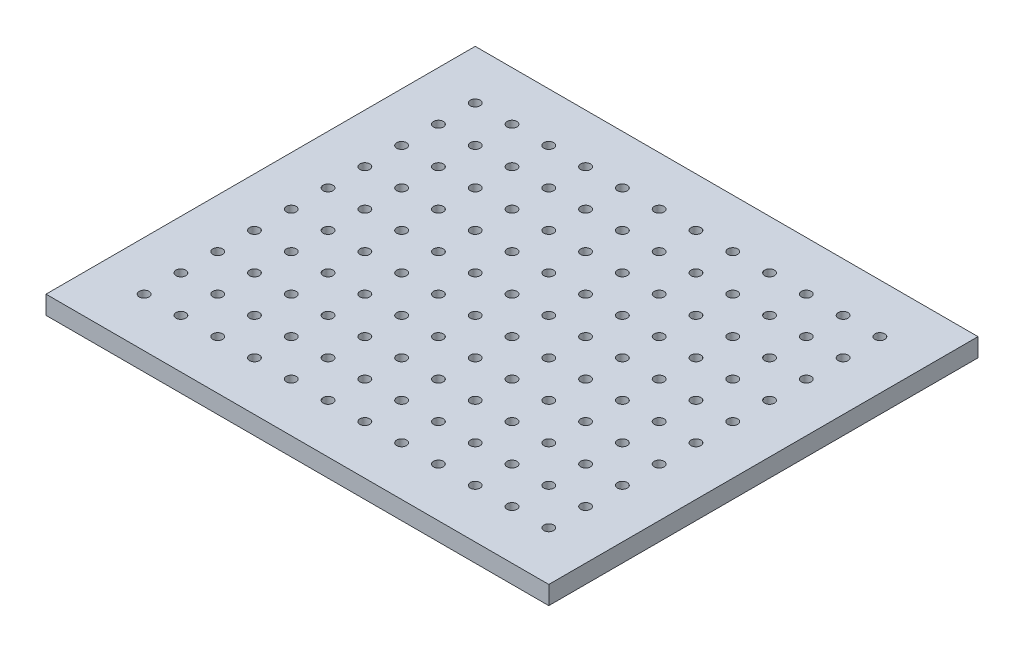
SolidWorks part; units mm, degrees
material "Balsa"
ref_plane "Plano frontal" through (0, 0, 0) normal (0, 0, 1) x (1, 0, 0)
ref_plane "Plano superior" through (0, 0, 0) normal (0, 1, 0) x (1, 0, 0)
ref_plane "Plano direito" through (0, 0, 0) normal (1, 0, 0) x (0, 0, -1)
sketch "Esboço1" plane through (0, 0, 0) normal (0, 1, 0) x (1, 0, 0)
  line L1 (-205, -175) -> (205, -175)
  line L2 (-205, -175) -> (-205, 175)
  line L3 (-205, 175) -> (205, 175)
  line L4 (205, -175) -> (205, 175)
  line L5 (-205, -175) -> (205, 175) construction
  line L6 (-205, 175) -> (205, -175) construction
  point P0 (0, 0)
  dimension "D1" = 350
  dimension "D2" = 410
extrude "Ressalto-extrusão1" add sketch "Esboço1" along normal blind 15
sketch "Esboço2" plane through (0, 15, 0) normal (0, 1, 0) x (1, 0, 0)
  line L0 (-205, -175) -> (205, -175) construction
  line L1 (-205, 175) -> (-205, -175) construction
  circle A0 centre (-165, -135) radius 4
  dimension "D1" = 8
  dimension "D2" = 40
  dimension "D3" = 40
extrude "Corte-extrusão1" cut sketch "Esboço2" against normal through all
pattern_linear "Padrão linear1" count 12 spacing 30 along (1, 0, 0) count 10 spacing 30 along (0, 0, -1) of "Corte-extrusão1"
ref_plane "Plane1" through (0, 0, 0) normal (0, 0, 1) x (1, 0, 0)
